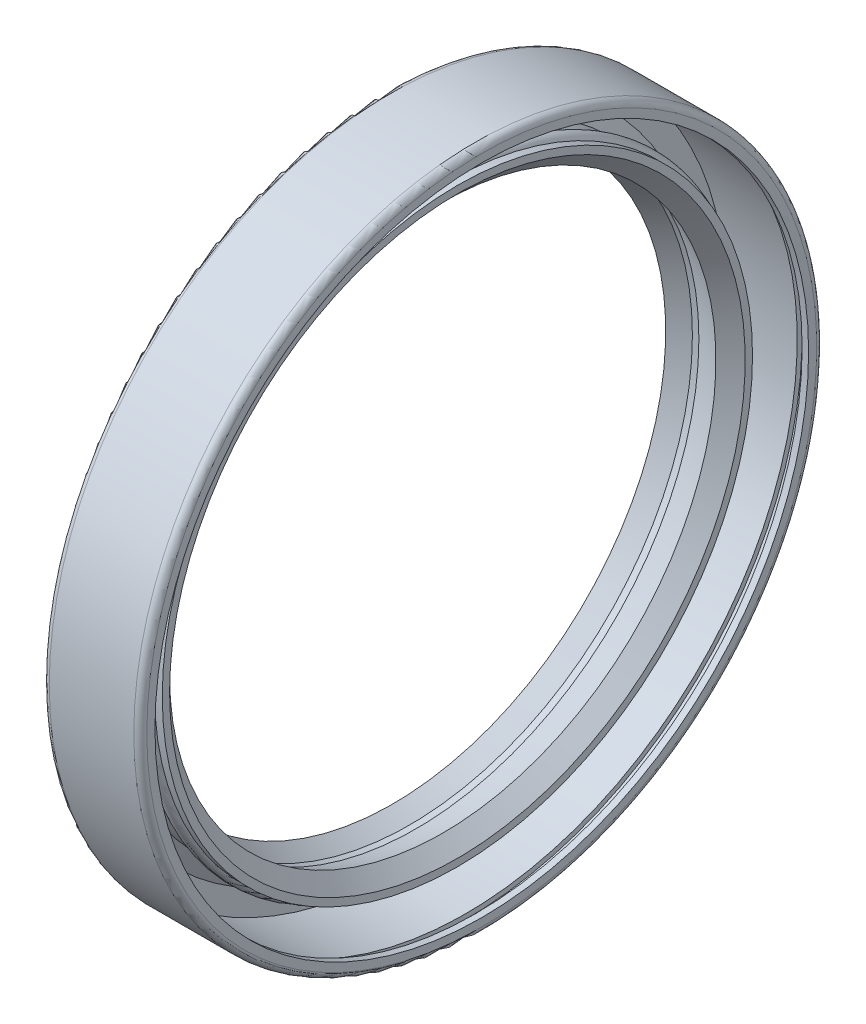
SolidWorks part; units mm, degrees
ref_plane "Plan1" through (0, 0, 0) normal (0, 0, 1) x (1, 0, 0)
ref_plane "Plan2" through (0, 0, 0) normal (0, 1, 0) x (1, 0, 0)
ref_plane "Plan3" through (0, 0, 0) normal (1, 0, 0) x (0, 0, -1)
sketch "Esquisse1" plane through (0, 0, 0) normal (0, 1, 0) x (1, 0, 0)
  line L0 (0, 0) -> (4.1667, 0) construction
  line L1 (0, 15.683) -> (0, 17.1667)
  line L2 (0.3333, 17.5) -> (4.6667, 17.5)
  line L3 (4.1667, 17) -> (4.1667, 17.25)
  line L4 (4.1667, 17) -> (0.5, 17)
  line L5 (0.5, 17) -> (0.5, 15.817)
  line L6 (0, 15.683) -> (0.25, 15.25)
  line L7 (0.25, 15.25) -> (0, 15.25)
  line L8 (0, 15.25) -> (0, 14.8333)
  line L9 (4.1667, 17.25) -> (4.6667, 17.25)
  line L10 (1.6263, 14.5) -> (1.2936, 14.5)
  line L11 (4.6667, 17.25) -> (4.6667, 16.75)
  line L12 (5, 16.75) -> (5, 17.1667)
  line L13 (4.6667, 16.75) -> (5, 16.75)
  line L14 (1.6263, 14.5) -> (3, 14)
  line L15 (3, 14) -> (3.75, 14.75)
  line L16 (3.75, 14.75) -> (3.75, 15.125)
  line L17 (3.75, 15.125) -> (3.3536, 15.125)
  line L18 (0.5, 15.817) -> (0.9717, 15)
  line L19 (1.2936, 14.5) -> (0.4276, 14)
  line L20 (0.4276, 14) -> (0.25, 14.3075)
  line L21 (0.25, 14.3075) -> (0.5833, 14.5)
  line L22 (0.9717, 15) -> (2.625, 15)
  line L23 (0.5833, 14.5) -> (0.3333, 14.5)
  arc A0 (0, 17.1667) -> (0.3333, 17.5) centre (0.3333, 17.1667) cw
  arc A1 (3.3536, 15.125) -> (2.625, 15) centre (3, 15) ccw
  arc A2 (4.6667, 17.5) -> (5, 17.1667) centre (4.6667, 17.1667) cw
  arc A3 (0, 14.8333) -> (0.3333, 14.5) centre (0.3333, 14.8333) ccw
  point P13 (0, 17.5)
  point P22 (5, 17.5)
  dimension "r" = 0.3333
  dimension "l" = 0.75
  dimension "D1" = 120
  dimension "De" = 17.5
  dimension "b" = 5
  dimension "e" = 0.5
  dimension "D7" = 45
  dimension "D6" = 20
  dimension "Di" = 14
  dimension "pl" = 3.75
  dimension "D16" = 60
  dimension "h" = 0.125
revolve "Base-Révolution" add sketch "Esquisse1" angle 360 about L0
equation "\"e@Esquisse1\" = \"b@Esquisse1\"/10"
equation "\"i@Esquisse1\"=\"e@Esquisse1\"/2"
equation "\"r@Esquisse1\"=\"e@Esquisse1\"*2/3"
equation "\"l@Esquisse1\"=\"i@Esquisse1\"*3"
equation "\"pl@Esquisse1\"=\"b@Esquisse1\"*3/4"
equation "\"h@Esquisse1\"=\"i@Esquisse1\"/2"
